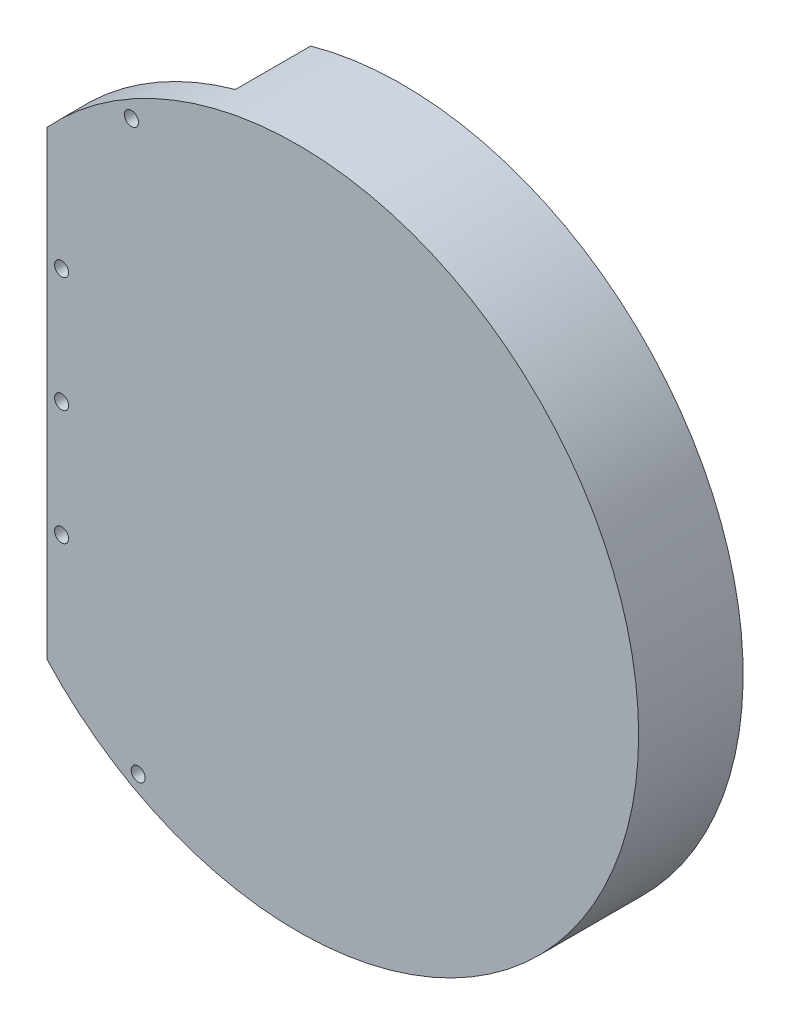
SolidWorks part; units mm, degrees
ref_plane "Front Plane" through (0, 0, 0) normal (0, 0, 1) x (1, 0, 0)
ref_plane "Top Plane" through (0, 0, 0) normal (0, 1, 0) x (1, 0, 0)
ref_plane "Right Plane" through (0, 0, 0) normal (1, 0, 0) x (0, 0, -1)
sketch "Sketch1" plane through (0, 0, 0) normal (0, 0, 1) x (1, 0, 0)
  line L0 (0, -39.4175) -> (0, 39.4175)
  arc A0 (0, 39.4175) -> (0, -39.4175) centre (42.9355, 0) cw
  point P4 (0, 0)
  point P6 (101.221, 0)
  dimension "D1" = 78.835
  dimension "D2" = 101.221
extrude "Boss-Extrude1" add sketch "Sketch1" along normal blind 5
sketch "Sketch2" plane through (0, 0, 5) normal (0, 0, 1) x (1, 0, 0)
  line L0 (0, 39.4175) -> (0, -39.4175) construction
  line L1 (0, 39.4175) -> (0, -39.4175) construction
  line L2 (5, 37.4198) -> (5, -37.4198) construction
  line L3 (0, 39.4175) -> (21.901, 39.4175) construction
  line L4 (21.901, 39.4175) -> (27.2366, 56.1315) construction
  line L5 (0, 0) -> (5, 0) construction
  line L6 (2.5, 41.9782) -> (2.5, -41.9782) construction
  line L7 (2.5, 0) -> (2.5, 39.4175) construction
  line L8 (2.5, -39.4175) -> (2.5, 0) construction
  line L9 (14.4504, 45.0327) -> (14.4504, 50.8507) construction
  line L10 (27.955, -51.1364) -> (27.955, -56.3275) construction
  line L11 (15.6031, -45.7414) -> (15.6031, -51.4795) construction
  arc A0 (0, -39.4175) -> (0, 39.4175) centre (42.9355, 0) ccw construction
  arc A1 (0, -39.4175) -> (0, 39.4175) centre (42.9355, 0) ccw construction
  arc A2 (5, -37.4198) -> (5, 37.4198) centre (42.9355, 0) ccw construction
  circle A3 centre (2.5, 19.7088) radius 1.2
  circle A4 centre (2.5, 0) radius 1.2
  circle A5 centre (2.5, -19.7087) radius 1.2
  circle A6 centre (14.4504, 47.9417) radius 1.2
  circle A7 centre (15.6031, -48.6105) radius 1.2
  arc A8 (5, 37.4198) -> (25.3782, 50.3099) centre (42.9355, 0) cw construction
  arc A9 (5, -37.4198) -> (27.955, -51.1364) centre (42.9355, 0) ccw construction
  point P14 (2.5, 0)
  point P24 (2.5, 0)
  dimension "D1" = 5
  dimension "D4" = 2.4
  dimension "D2" = 21.901
  dimension "D3" = 107.705
  dimension "D5" = 27.955
extrude "Cut-Extrude1" cut sketch "Sketch2" against normal through all
sketch "Sketch3" plane through (0, 0, 5) normal (0, 0, 1) x (1, 0, 0)
  line L0 (27.955, -56.3275) -> (27.955, -51.1364)
  line L1 (25.3782, 50.3099) -> (27.2366, 56.1315)
  arc A0 (25.3782, 50.3099) -> (27.955, -51.1364) centre (42.9355, 0) cw
  arc A1 (27.955, -56.3275) -> (27.2366, 56.1315) centre (42.9355, 0) ccw
  arc A2 (5, -37.4198) -> (5, 37.4198) centre (42.9355, 0) ccw construction
  arc A3 (0, -39.4175) -> (0, 39.4175) centre (42.9355, 0) ccw construction
extrude "Boss-Extrude2" add sketch "Sketch3" against normal blind 12.879 from surface at -5 starting at face at (15.6504, 47.9417, 0)
equation "\"width\"=0.101221"
equation "\"height\"=0.078835"
equation "\"stop_width\"=0.005000"
equation "\"inf_stop_x\"=0.027955"
equation "\"superior_stop_x\"=0.021901"
equation "\"superior_stop_angle\"=107.704683"
equation "\"t1\"=0.005000"
equation "\"t2\"=0.012879"
equation "\"cover_holes_diam\"=0.002400"
equation "\"cover_holes_depth\"=0.004000"
equation "\"cover_hole_pitch\"=0.000400"
equation "\"D1@Sketch1\"=\"height\"*1000"
equation "\"D2@Sketch1\"=\"width\"*1000"
equation "\"D1@Boss-Extrude1\"=\"t1\"*1000"
equation "\"D1@Sketch2\"=\"stop_width\"*1000"
equation "\"D2@Sketch2\"=\"superior_stop_x\"*1000"
equation "\"D3@Sketch2\"=\"superior_stop_angle\""
equation "\"D4@Sketch2\"=\"cover_holes_diam\"*1000"
equation "\"D5@Sketch2\"=\"inf_stop_x\"*1000"
equation "\"D1\"= \"cover_holes_depth\" * 1000"
equation "\"D1@Boss-Extrude2\"=\"t2\"*1000"
